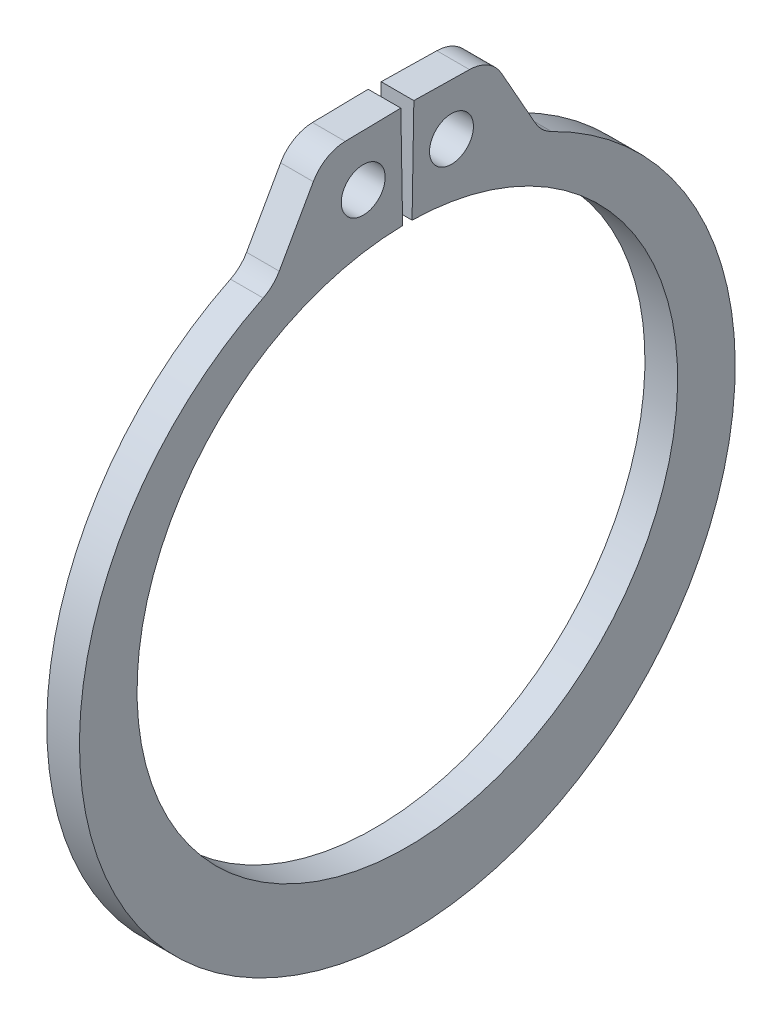
SolidWorks part; units mm, degrees
material "Cast Carbon Steel"
ref_plane "Front" through (0, 0, 0) normal (0, 0, 1) x (1, 0, 0)
ref_plane "Top" through (0, 0, 0) normal (0, 1, 0) x (1, 0, 0)
ref_plane "Right" through (0, 0, 0) normal (1, 0, 0) x (0, 0, -1)
sketch "Sketch1" plane through (0, 0, 0) normal (1, 0, 0) x (0, 0, -1)
  line L0 (0, 0) -> (0, 7.3533) construction
  line L1 (-0.1283, 7.3522) -> (-0.1771, 10.1458)
  line L2 (0.1771, 10.1458) -> (2.2723, 10.1092)
  line L3 (2.2723, 10.1092) -> (3.6441, 7.6751)
  line L4 (0.1283, 7.3522) -> (0.1771, 10.1458)
  line L5 (-0.1771, 10.1458) -> (-2.2723, 10.1092)
  line L6 (-2.2723, 10.1092) -> (-3.6441, 7.6751)
  line L7 (-3.6441, 7.6751) -> (-3.1539, 6.6426) construction
  line L8 (3.6441, 7.6751) -> (3.1539, 6.6426) construction
  line L9 (0, -7.3533) -> (0, -9.3853) construction
  line L10 (-2.2723, 10.1092) -> (-0.1283, 7.3522) construction
  line L11 (0, 7.3533) -> (0, 10.1473) construction
  line L12 (-7.3533, 0) -> (7.3533, 0) construction
  circle A0 centre (0, 0) radius 7.3533 construction
  arc A1 (-0.1283, 7.3522) -> (0.1283, 7.3522) centre (0, 0) ccw
  circle A3 centre (0, 0) radius 11.2395 construction
  circle A4 centre (-1.2003, 8.7307) radius 0.5969
  circle A5 centre (1.2003, 8.7307) radius 0.5969
  arc A6 (-3.6441, 7.6751) -> (3.6441, 7.6751) centre (0, -0.4659) ccw
  point P0 (0, -9.3853)
  dimension "A" = 14.7066
  dimension "D2" = 2.0955
  dimension "L" = 22.479
  dimension "Hole" = 1.1938
  dimension "Smin" = 1.143
  dimension "Smax" = 2.032
  dimension "H" = 2.794
  dimension "Angle" = 1
extrude "Extrude1" add sketch "Sketch1" along normal mid plane 0.889
fillet "Fillet1" radius 1.016 4 edges at (0, 7.6751, 3.6441) (0, 7.6751, -3.6441) (0, 10.1092, 2.2723) (0, 10.1092, -2.2723)
sketch "Sketch2" plane through (0, 0, 0) normal (0, 0, 1) x (1, 0, 0)
  line L0 (-4.9403, 0) -> (12.8397, 0)
  line L1 (12.8397, 0) -> (12.8397, -7.9375)
  line L2 (-0.4953, -7.9375) -> (-4.4704, -7.9375)
  line L3 (12.8397, -7.9375) -> (0.4953, -7.9375)
  line L4 (0.4953, -7.9375) -> (0.4953, -7.4676)
  line L5 (0.4953, -7.4676) -> (-0.4953, -7.4676)
  line L6 (-0.4953, -7.4676) -> (-0.4953, -7.9375)
  line L7 (-0.4953, -7.9375) -> (-4.9403, -7.9375) construction
  line L8 (-4.9403, -7.9375) -> (-4.9403, 0) construction
  line L9 (12.8397, 0) -> (76.391, 0) construction
  line L10 (-4.4704, -7.9375) -> (-4.9403, -7.4676)
  line L11 (-4.9403, -7.4676) -> (-4.9403, 0)
  point P10 (0, -7.4676)
  dimension "D1" = 45
  dimension "Dg" = 14.9352
  dimension "Ds" = 15.875
  dimension "W" = 0.9906
  dimension "D2" = 17.78
  dimension "D3" = 4.445
revolve "Revolve1" [suppressed] add sketch "Sketch2" angle 360 about L9
delete or keep bodies "Body-Delete1" [suppressed] type delete bodies bodies 122
equation "\"D2@Sketch2\" = \"D1@Extrude1\"*20"
equation "\"D3@Sketch2\" = \"D2@Sketch2\"/4"
equation "\"D2@Sketch1\" = \"H@Sketch1\"*.75"
